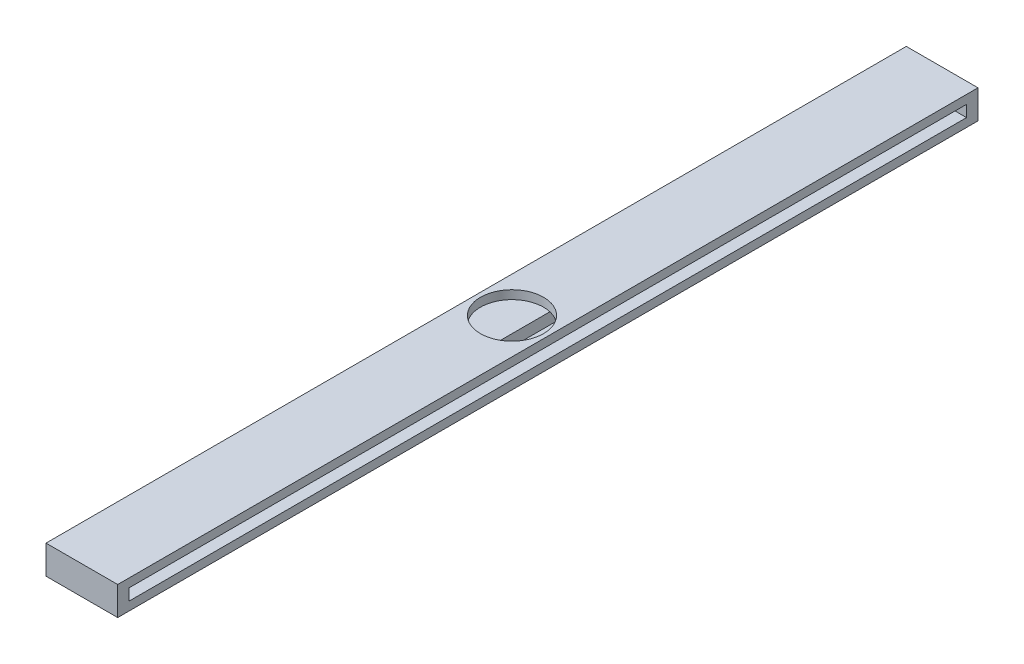
SolidWorks part; units mm, degrees
ref_plane "前视基准面" through (0, 0, 0) normal (0, 0, 1) x (1, 0, 0)
ref_plane "上视基准面" through (0, 0, 0) normal (0, 1, 0) x (1, 0, 0)
ref_plane "右视基准面" through (0, 0, 0) normal (1, 0, 0) x (0, 0, -1)
other "Configuration Table"
sketch "草图1" plane through (0, 0, 0) normal (0, 1, 0) x (1, 0, 0)
  line L1 (-62.3362, 84.2911) -> (-47.3362, 84.2911)
  line L2 (-62.3362, 84.2911) -> (-62.3362, -215.7089)
  line L3 (-62.3362, -215.7089) -> (-47.3362, -215.7089)
  line L4 (-47.3362, 84.2911) -> (-47.3362, -215.7089)
  dimension "D1" = 300
  dimension "D2" = 15
extrude "凸台-拉伸1" add sketch "草图1" along normal blind 4
sketch "草图2" plane through (-47.3362, 0, 0) normal (1, 0, 0) x (0, 0, -1)
  line L7 (-215.7089, 4) -> (-211.7089, 4)
  line L8 (-215.7089, 4) -> (-215.7089, 0)
  line L9 (-215.7089, 0) -> (-211.7089, 0)
  line L10 (-211.7089, 4) -> (-211.7089, 0)
  line L11 (-215.7089, 0) -> (84.2911, 0) construction
  line L13 (84.2911, 4) -> (80.2911, 4)
  line L14 (84.2911, 4) -> (84.2911, 0)
  line L15 (84.2911, 0) -> (80.2911, 0)
  line L16 (80.2911, 4) -> (80.2911, 0)
  dimension "D1" = 4
  dimension "D2" = 4
  dimension "D3" = 4
  dimension "D4" = 4
extrude "凸台-拉伸2" add sketch "草图2" along normal blind 10
sketch "草图3" plane through (0, 4, 0) normal (0, 1, 0) x (1, 0, 0)
  line L1 (-62.3362, 84.2911) -> (-37.3362, 84.2911)
  line L2 (-62.3362, 84.2911) -> (-62.3362, -215.7089)
  line L3 (-62.3362, -215.7089) -> (-37.3362, -215.7089)
  line L4 (-37.3362, 84.2911) -> (-37.3362, -215.7089)
  dimension "D1" = 300
  dimension "D2" = 25
extrude "凸台-拉伸3" add sketch "草图3" along normal blind 3
sketch "草图4" plane through (0, 0, 0) normal (0, -1, 0) x (1, 0, 0)
  line L1 (-62.3362, 215.7089) -> (-37.3362, 215.7089)
  line L2 (-62.3362, 215.7089) -> (-62.3362, -84.2911)
  line L3 (-62.3362, -84.2911) -> (-37.3362, -84.2911)
  line L4 (-37.3362, 215.7089) -> (-37.3362, -84.2911)
  dimension "D1" = 300
  dimension "D2" = 25
extrude "凸台-拉伸4" add sketch "草图4" along normal blind 3
sketch "草图5" plane through (0, 7, 0) normal (0, 1, 0) x (1, 0, 0)
  line L0 (-62.3362, -215.7089) -> (-37.3362, -215.7089) construction
  line L1 (-37.3362, -215.7089) -> (-37.3362, 84.2911) construction
  circle A0 centre (-49.8362, -65.7089) radius 11
  dimension "D1" = 150
  dimension "D2" = 12.5
extrude "切除-拉伸1" cut sketch "草图5" against normal blind 3
